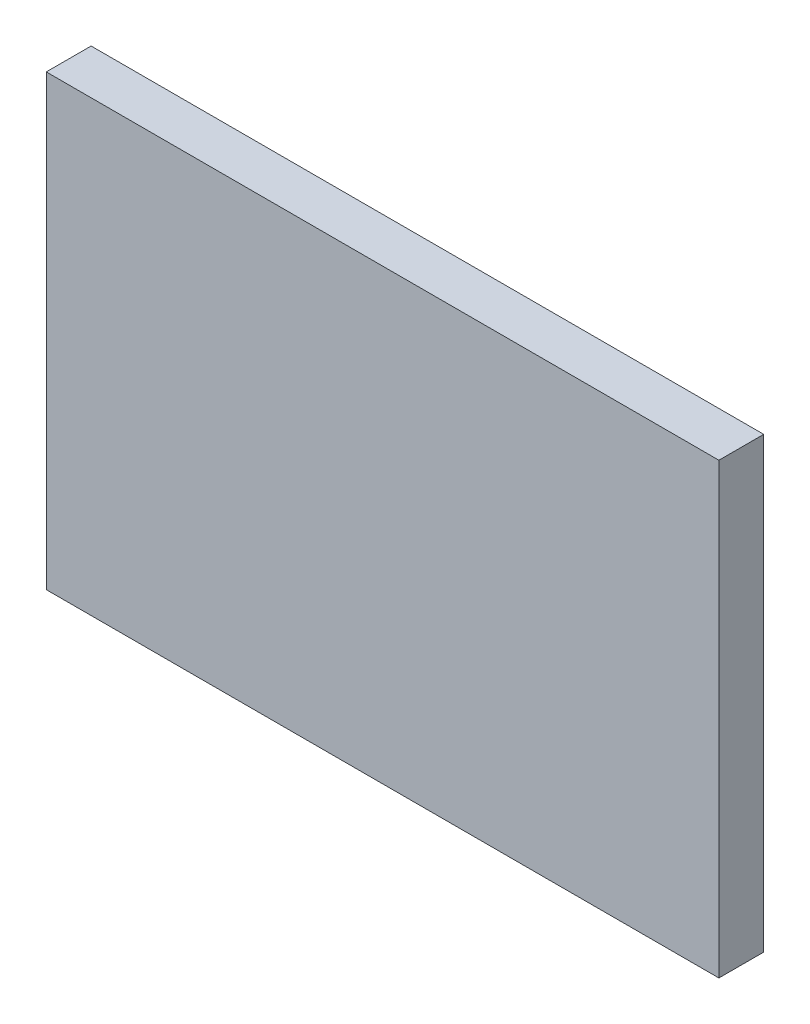
SolidWorks part; units mm, degrees
ref_plane "Front Plane" through (0, 0, 0) normal (0, 0, 1) x (1, 0, 0)
ref_plane "Top Plane" through (0, 0, 0) normal (0, 1, 0) x (1, 0, 0)
ref_plane "Right Plane" through (0, 0, 0) normal (1, 0, 0) x (0, 0, -1)
sketch "Sketch1" plane through (0, 0, 0) normal (0, 0, 1) x (1, 0, 0)
  line L1 (0, 0) -> (30, 0)
  line L2 (0, 0) -> (0, 20)
  line L3 (0, 20) -> (30, 20)
  line L4 (30, 0) -> (30, 20)
extrude "Boss-Extrude1" add sketch "Sketch1" along normal blind 2
